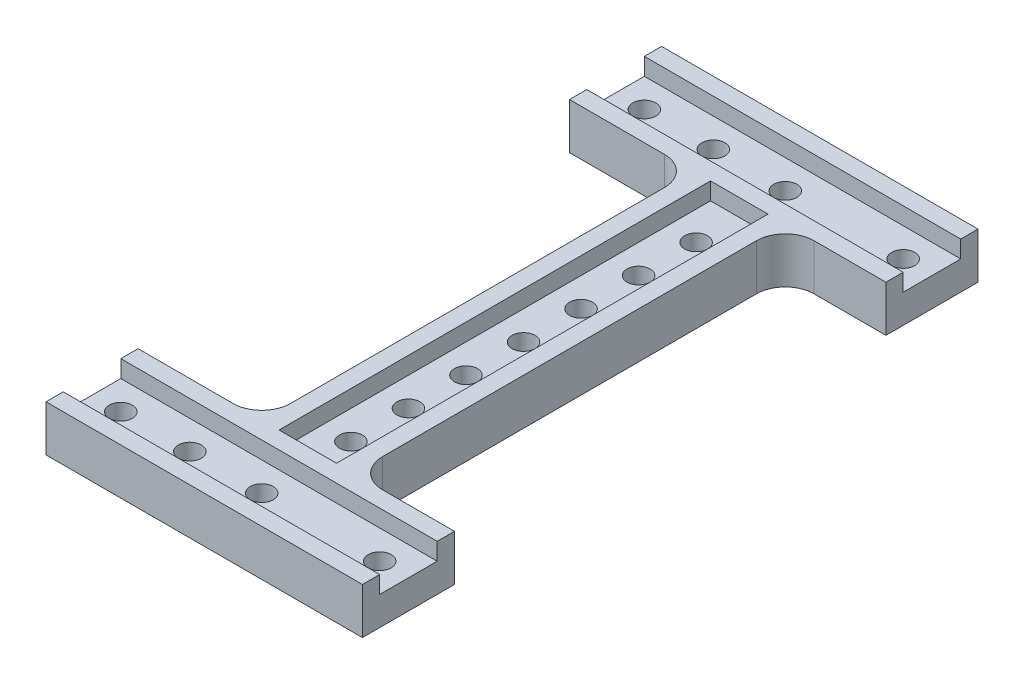
SolidWorks part; units mm, degrees
ref_plane "Front Plane" through (0, 0, 0) normal (0, 0, 1) x (1, 0, 0)
ref_plane "Top Plane" through (0, 0, 0) normal (0, 1, 0) x (1, 0, 0)
ref_plane "Right Plane" through (0, 0, 0) normal (1, 0, 0) x (0, 0, -1)
sketch "Sketch1" plane through (0, 0, 0) normal (0, 1, 0) x (1, 0, 0)
  line L1 (-36.2516, 11.0214) -> (18.7484, 11.0214)
  line L2 (-36.2516, 11.0214) -> (-36.2516, -4.9786)
  line L3 (-36.2516, -4.9786) -> (18.7484, -4.9786)
  line L4 (18.7484, 11.0214) -> (18.7484, -4.9786)
  line L6 (-19.2516, -4.9786) -> (-6.7516, -4.9786)
  circle A0 centre (-19.2516, 3.0214) radius 2
  circle A1 centre (-6.7516, 3.0214) radius 2
extrude "Boss-Extrude1" add sketch "Sketch1" along normal blind 5 contours L4 L1 L2 L3 A1 A0
sketch "Sketch2" plane through (0, 5, 0) normal (0, 1, 0) x (1, 0, 0)
  line L0 (-36.2516, 11.0214) -> (-36.2516, 8.0214)
  line L1 (-36.2516, 11.0214) -> (-36.2516, -4.9786) construction
  line L2 (-36.2516, 8.0214) -> (18.7484, 8.0214)
  line L3 (18.7484, 11.0214) -> (18.7484, -4.9786) construction
  line L4 (18.7484, 8.0214) -> (18.7484, 11.0214)
  line L5 (18.7484, 11.0214) -> (-36.2516, 11.0214)
  line L6 (-36.2516, -4.9786) -> (-36.2516, -1.9786)
  line L7 (-36.2516, -1.9786) -> (18.7484, -1.9786)
  line L8 (18.7484, -1.9786) -> (18.7484, -4.9786)
  line L9 (18.7484, -4.9786) -> (-36.2516, -4.9786)
extrude "Boss-Extrude2" add sketch "Sketch2" along normal blind 3
sketch "Sketch4" plane through (0, 0, 0) normal (0, -1, 0) x (1, 0, 0)
  line L1 (-36.2516, 95.9786) -> (18.7484, 95.9786)
  line L3 (18.7484, 95.9786) -> (18.7484, 79.9786)
  line L4 (18.7484, 79.9786) -> (-36.2516, 79.9786)
  line L5 (-36.2516, 79.9786) -> (-36.2516, 95.9786)
  circle A0 centre (-19.2516, 87.9786) radius 2
  circle A1 centre (-6.7516, 87.9786) radius 2
extrude "Boss-Extrude3" add sketch "Sketch4" against normal blind 5 separate body
sketch "Sketch5" plane through (0, 5, 0) normal (0, 1, 0) x (1, 0, 0)
  line L0 (18.7484, -95.9786) -> (18.7484, -92.9786)
  line L1 (18.7484, -79.9786) -> (18.7484, -95.9786) construction
  line L2 (18.7484, -92.9786) -> (-36.2516, -92.9786)
  line L3 (-36.2516, -95.9786) -> (-36.2516, -79.9786) construction
  line L4 (-36.2516, -92.9786) -> (-36.2516, -95.9786)
  line L5 (-36.2516, -95.9786) -> (18.7484, -95.9786)
  line L6 (-36.2516, -79.9786) -> (-36.2516, -82.9786)
  line L7 (-36.2516, -82.9786) -> (18.7484, -82.9786)
  line L8 (18.7484, -82.9786) -> (18.7484, -79.9786)
  line L9 (18.7484, -79.9786) -> (-36.2516, -79.9786)
extrude "Boss-Extrude4" add sketch "Sketch5" along normal blind 3
sketch "Sketch6" plane through (0, 0, 0) normal (0, -1, 0) x (1, 0, 0)
  line L1 (-36.2516, 79.9786) -> (18.7484, 79.9786) construction
  line L2 (-6.7516, 79.9786) -> (1.2484, 79.9786)
  line L3 (1.2484, 79.9786) -> (1.2484, 4.9786)
  line L4 (-36.2516, 4.9786) -> (18.7484, 4.9786) construction
  line L5 (1.2484, 4.9786) -> (-14.7516, 4.9786)
  line L6 (-14.7516, 4.9786) -> (-14.7516, 79.9786)
  line L7 (-14.7516, 79.9786) -> (-6.7516, 79.9786)
extrude "Boss-Extrude5" add sketch "Sketch6" against normal blind 5
sketch "Sketch7" plane through (0, 5, 0) normal (0, 1, 0) x (1, 0, 0)
  line L0 (1.2484, -79.9786) -> (-1.7516, -79.9786)
  line L1 (1.2484, -79.9786) -> (-14.7516, -79.9786) construction
  line L2 (-1.7516, -79.9786) -> (-1.7516, -4.9786)
  line L3 (-14.7516, -4.9786) -> (1.2484, -4.9786) construction
  line L4 (-1.7516, -4.9786) -> (1.2484, -4.9786)
  line L5 (1.2484, -4.9786) -> (1.2484, -79.9786)
  line L6 (-14.7516, -79.9786) -> (-11.7516, -79.9786)
  line L7 (-11.7516, -79.9786) -> (-11.7516, -4.9786)
  line L8 (-11.7516, -4.9786) -> (-14.7516, -4.9786)
  line L9 (-14.7516, -4.9786) -> (-14.7516, -79.9786)
extrude "Boss-Extrude6" add sketch "Sketch7" along normal blind 3
sketch "Sketch8" plane through (0, 0, 0) normal (0, -1, 0) x (1, 0, 0)
  circle A0 centre (13.7484, -3.0214) radius 2
  circle A1 centre (13.7484, 87.9786) radius 2
extrude "Cut-Extrude2" cut sketch "Sketch8" against normal up to surface (5 mm away) up to face at (-6.7516, 5, 85.9786)
sketch "Sketch10" plane through (0, 0, 0) normal (0, -1, 0) x (1, 0, 0)
  circle A0 centre (-19.2516, -3.0214) radius 4
  circle A1 centre (-6.7516, -3.0214) radius 4
  circle A2 centre (13.7484, -3.0214) radius 4
  circle A3 centre (-19.2516, 87.9786) radius 4
  circle A4 centre (-6.7516, 87.9786) radius 4
  circle A5 centre (13.7484, 87.9786) radius 4
extrude "Cut-Extrude3" cut sketch "Sketch10" against normal blind 2
sketch "Sketch11" plane through (0, 0, 0) normal (0, -1, 0) x (1, 0, 0)
  circle A0 centre (-31.2516, -3.0214) radius 2
  circle A1 centre (-31.2516, 87.9786) radius 2
extrude "Cut-Extrude4" cut sketch "Sketch11" against normal up to surface (5 mm away) up to face at (-6.7516, 5, 42.4786)
sketch "Sketch12" plane through (0, 5, 0) normal (0, 1, 0) x (1, 0, 0)
  circle A0 centre (-6.7516, -12.4786) radius 2
  circle A1 centre (-6.7516, -22.4786) radius 2
  circle A2 centre (-6.7516, -32.4786) radius 2
  circle A3 centre (-6.7516, -42.4786) radius 2
  circle A4 centre (-6.7516, -52.4786) radius 2
  circle A5 centre (-6.7516, -62.4786) radius 2
  circle A6 centre (-6.7516, -72.4786) radius 2
extrude "Cut-Extrude5" cut sketch "Sketch12" against normal up to surface (5 mm away) up to face at (-31.2516, 0, -5.0214)
fillet "Fillet1" radius 5 4 edges at (-14.7516, 4, 79.9786) (1.2484, 4, 79.9786) (1.2484, 4, 4.9786) (-14.7516, 4, 4.9786)
